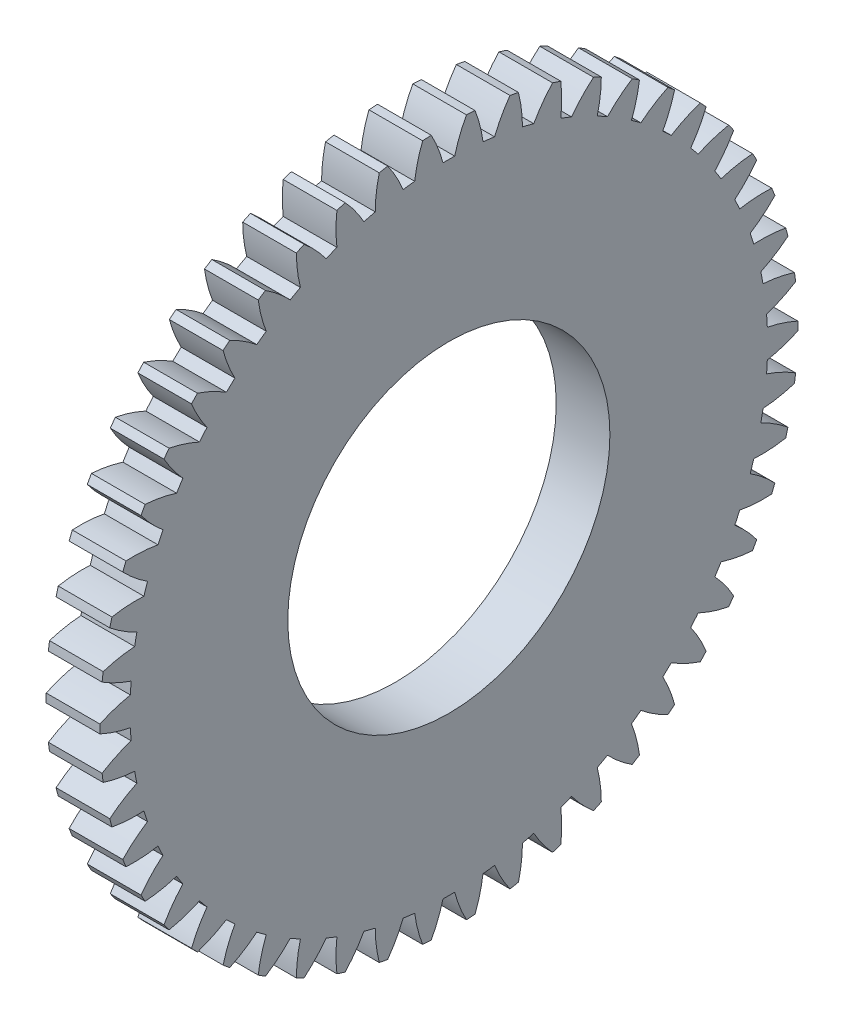
SolidWorks part; units mm, degrees
ref_plane "Plane1" through (0, 0, 0) normal (0, 0, 1) x (1, 0, 0)
ref_plane "Plane2" through (0, 0, 0) normal (0, 1, 0) x (1, 0, 0)
ref_plane "Plane3" through (0, 0, 0) normal (1, 0, 0) x (0, 0, -1)
other "Configuration Table"
sketch "HoldingSke" plane through (0, 0, 0) normal (0, 1, 0) x (1, 0, 0)
  line L0 (0, 0) -> (0.5142, -0.6128)
  line L1 (-15, 0) -> (100, 0) construction
  line L2 (0, 0) -> (-2.1039, 2.3779)
  line L3 (0, 0) -> (-11.863, 4.5341)
  line L4 (0, 0) -> (5.5511, 6.6156)
  line L5 (0, 0) -> (-46.8476, -17.4728)
  line L6 (0, 0) -> (-4.1448, -2.7965)
  line L7 (-2.1039, 2.3779) -> (8.6586, 51.2059)
  line L8 (-76.2, 54.61) -> (-72.9, 54.61)
  line L9 (-71.009, 38.7566) -> (-53.1078, 45.2721)
  line L10 (-76.2, 71.12) -> (104.1128, 71.12)
  line L11 (0, 0) -> (-5, 0)
  line L12 (-76.2, 101.6) -> (-76.155, 101.6)
  line L13 (24.9733, 27.94) -> (52.9518, 28.4284)
  line L14 (24.9733, 27.94) -> (24.9743, 27.94)
  line L15 (24.9733, 27.94) -> (100.4006, 29.5858)
  line L16 (-63.627, -1.25) -> (-12.827, -1.25)
  circle A0 centre (0, 0) radius 15
  circle A1 centre (0, 0) radius 29.6865
  circle A2 centre (0, 0) radius 37.5
  circle A3 centre (0, 0) radius 15
  dimension "MHD" = 59.373
  dimension "Hub_dia" = 75
  dimension "Bore" = 30
  dimension "MBD" = 30
  dimension "Num_teeth" = 50
  dimension "Pitch" = 0.8
  dimension "Overall_len" = 50
  dimension "Show_teeth" = 50
  dimension "Thickness" = 5
  dimension "OAL" = 50.0001
  dimension "T_dim" = 3.3
  dimension "Ap" = 20
  dimension "H" = 19.05
  dimension "Pitch_radius" = 180.3128
  dimension "Width" = 5
  dimension "Backlash" = 0.045
  dimension "Addendum_fac" = 1
  dimension "Dedendum_fac" = 1.25
  dimension "Clearance_fac" = 0.25
  dimension "Dedendum_add" = 0.001
  dimension "Module" = 1.25
sketch "BasProSke" plane through (0, 0, 0) normal (0, 1, 0) x (1, 0, 0)
  line L0 (-10, 0) -> (60, 0) construction
  line L1 (0, 0) -> (0, 32.5)
  line L2 (0, 0) -> (5, 0)
  line L3 (5, 0) -> (5, 32.5)
  line L4 (5, 32.5) -> (0, 32.5)
  dimension "Thickness" = 5
  dimension "Diameter" = 65
revolve "Base-Revolve" add sketch "BasProSke" angle 360 about L0
sketch "TooCutSke" plane through (0, 0, 0) normal (1, 0, 0) x (0, 0, -1)
  line L1 (0, 0) -> (0, 107) construction
  line L2 (0, 0) -> (-1.0603, 31.232) construction
  line L3 (0, 0) -> (-3.9228, 62.3506) construction
  line L4 (-1.0603, 31.232) -> (-1.9614, 31.1753) construction
  arc A0 (0.543, 29.6815) -> (-0.543, 29.6815) centre (0, 0) ccw
  arc A1 (1.6539, 32.4833) -> (-1.6539, 32.4833) centre (0, 0) ccw
  circle A2 centre (0, 0) radius 31.25 construction
  circle A3 centre (0, 0) radius 29.3654 construction
  arc A4 (-0.543, 29.6815) -> (-1.6539, 32.4833) centre (-12.6336, 26.5088) ccw
  arc A5 (1.6539, 32.4833) -> (0.543, 29.6815) centre (12.6336, 26.5088) ccw
  dimension "Root_dia" = 59.373
  dimension "Overcut_dia" = 65.0508
  dimension "Pitch_dia" = 62.5
  dimension "Base_dia" = 58.7308
  dimension "Flank_rad" = 12.5
  dimension "Half_ang" = 3.6
  dimension "Half_CT" = 0.9028
extrude "ToothCut" cut sketch "TooCutSke" along normal through all
fillet "Breaks" [suppressed] radius 0.025
fillet "RootFillets" [suppressed] radius 0.3135
pattern_circular "TeethCuts" count 50 every 7.2 about axis through (-10, 0, 0) along (1, 0, 0) of "ToothCut", "RootFillets", "Breaks"
sketch "HubNeaOneSke" plane through (0, 0, 0) normal (-1, 0, 0) x (0, 0, 1)
  circle A0 centre (0, 0) radius 29.6865
  dimension "Diameter" = 59.373
extrude "HubNearOne" [suppressed] add sketch "HubNeaOneSke" along normal blind 45.0001
sketch "HubNeaBotSke" plane through (0, 0, 0) normal (-1, 0, 0) x (0, 0, 1)
  circle A0 centre (0, 0) radius 29.6865
  dimension "Diameter" = 59.373
extrude "HubNearBoth" [suppressed] add sketch "HubNeaBotSke" along normal blind 22.5001
ref_plane "FarPln" through (5, 0, 0) normal (1, 0, 0) x (0, 0, -1)
sketch "HubFarSke" plane through (5, 0, 0) normal (1, 0, 0) x (0, 0, -1)
  circle A0 centre (0, 0) radius 29.6865
  dimension "Diameter" = 59.373
extrude "HubFar" [suppressed] add sketch "HubFarSke" along normal blind 22.5001
sketch "BorSke" plane through (0, 0, 0) normal (1, 0, 0) x (0, 0, -1)
  circle A0 centre (0, 0) radius 15
  dimension "Diameter" = 30
extrude "Bore" cut sketch "BorSke" along normal mid plane 100.0002
sketch "KeySke" plane through (0, 0, 0) normal (1, 0, 0) x (0, 0, -1)
  line L0 (-5, 0) -> (-5, 18.3)
  line L1 (-5, 18.3) -> (5, 18.3)
  line L2 (5, 18.3) -> (5, 0)
  line L3 (0, 0) -> (0, 34) construction
  line L4 (-5, 0) -> (5, 0)
  dimension "Offset" = 18.3
  dimension "Width" = 10
extrude "Keyway" [suppressed] cut sketch "KeySke" along normal mid plane 100.0002
pattern_circular "Keyway2" [suppressed] count 2 every 90 about axis through (-10, 0, 0) along (1, 0, 0)
equation "' \"Module@HoldingSke\" = 6.35"
equation "' \"Num_teeth@HoldingSke\" = 12"
equation "' \"Ap@HoldingSke\" =  20"
equation "' \"Ap@HoldingSke\" = 20"
equation "' \"Width@HoldingSke\" = 0.5 * 25.4"
equation "' \"Hub_dia@HoldingSke\"= 1 * 25.4"
equation "' \"Hub_dia@HoldingSke\" = 1 * 25.4"
equation "' \"Overall_len@HoldingSke\" = 1.0 * 25.4"
equation "' \"Bore@HoldingSke\" = 0.75 * 25.4"
equation "' \"T_dim@HoldingSke\" = 0.1 * 25.4"
equation "' \"Width@KeySke\" = 0.25 * 25.4"
equation "' \"Show_teeth@HoldingSke\" = 13"
equation "' \"Backlash@HoldingSke\" = 0.009 * 25.4"
equation "' \"Addendum_fac@HoldingSke\" = 1.0"
equation "' \"Dedendum_fac@HoldingSke\" = 1.25"
equation "' \"Dedendum_add@HoldingSke\" = 0.00005 * 25.4"
equation "' \"Clearance_fac@HoldingSke\" = 0.25"
equation "\"Pitch@HoldingSke\" = 1 / \"Module@HoldingSke\""
equation "\"Overcut_dia@TooCutSke\" = (\"Num_teeth@HoldingSke\" + 2 * \"Addendum_fac@HoldingSke\") / \"Pitch@HoldingSke\" + 0.002 * 25.4"
equation "\"Pitch_dia@TooCutSke\" = \"Num_teeth@HoldingSke\" / \"Pitch@HoldingSke\""
equation "\"Base_dia@TooCutSke\" = \"Num_teeth@HoldingSke\" / \"Pitch@HoldingSke\" * cos((\"Ap@HoldingSke\"  * 3.14159265 / 180))"
equation "\"Root_dia@TooCutSke\" = (\"Num_teeth@HoldingSke\" + 2) / \"Pitch@HoldingSke\" - 2 * (\"Addendum_fac@HoldingSke\" + \"Dedendum_fac@HoldingSke\") / \"Pitch@HoldingSke\" - \"Dedendum_add@HoldingSke\" * 2"
equation "\"Half_ang@TooCutSke\" = 180 / \"Num_teeth@HoldingSke\""
equation "\"Half_CT@TooCutSke\" = \"Num_teeth@HoldingSke\" / \"Pitch@HoldingSke\" * sin((3.14159265 / 2 / \"Num_teeth@HoldingSke\")) / 2 - 7 * \"Backlash@HoldingSke\" / 4"
equation "\"Flank_rad@TooCutSke\" = \"Num_teeth@HoldingSke\" / \"Pitch@HoldingSke\" / 5"
equation "\"Radius@RootFillets\" = \"Clearance_fac@HoldingSke\" / \"Pitch@HoldingSke\" + \"Dedendum_add@HoldingSke\""
equation "\"Break_rad@Breaks\" = 0.02 / \"Pitch@HoldingSke\""
equation "\"Thickness@HoldingSke\" = \"Width@HoldingSke\""
equation "\"OAL@HoldingSke\" = \"Thickness@HoldingSke\""
equation "\"MHD@HoldingSke\" = (\"Num_teeth@HoldingSke\" + 2) / \"Pitch@HoldingSke\" - 2 * (\"Addendum_fac@HoldingSke\" + \"Dedendum_fac@HoldingSke\")  / \"Pitch@HoldingSke\" - \"Dedendum_add@HoldingSke\" * 2"
equation "\"MBD@HoldingSke\" = (\"Num_teeth@HoldingSke\" + 2) / \"Pitch@HoldingSke\" - 2 * (\"Addendum_fac@HoldingSke\" + \"Dedendum_fac@HoldingSke\")  / \"Pitch@HoldingSke\" - \"Dedendum_add@HoldingSke\" * 2 - 0.002 * 25.4"
equation "\"MHD@HoldingSke\" = ((sgn( \"MHD@HoldingSke\" - \"Hub_dia@HoldingSke\" )-1)*( \"MHD@HoldingSke\" - \"Hub_dia@HoldingSke\" ))/-2+ \"Hub_dia@HoldingSke\""
equation "\"MBD@HoldingSke\" = ((sgn( \"MBD@HoldingSke\" - \"Bore@HoldingSke\" )-1)*( \"MBD@HoldingSke\" - \"Bore@HoldingSke\" ))/-2+ \"Bore@HoldingSke\""
equation "\"OAL@HoldingSke\" = ((sgn( \"OAL@HoldingSke\" - \"Overall_len@HoldingSke\" )+1)*( \"OAL@HoldingSke\" - \"Overall_len@HoldingSke\" ))/2 + \"Overall_len@HoldingSke\" + 0.000002 * 25.4"
equation "\"Num_teeth@TeethCuts\" = int( \"Show_teeth@HoldingSke\" ) + 1"
equation "\"Num_teeth@TeethCuts\" = ((sgn( \"Num_teeth@TeethCuts\" - \"Num_teeth@HoldingSke\" )-1)*( \"Num_teeth@TeethCuts\" - \"Num_teeth@HoldingSke\" ))/-2+ \"Num_teeth@HoldingSke\""
equation "\"Num_teeth@TeethCuts\" = ((sgn( \"Num_teeth@TeethCuts\" - 2.0)+1)*( \"Num_teeth@TeethCuts\" - 2.0))/2 +2.0"
equation "\"Angle@TeethCuts\" = 360.0 / \"Num_teeth@HoldingSke\""
equation "\"Diameter@BasProSke\" = (\"Num_teeth@HoldingSke\" + 2 * \"Addendum_fac@HoldingSke\") / \"Pitch@HoldingSke\""
equation "\"Thickness@BasProSke\"  = \"Thickness@HoldingSke\""
equation "' \"Fillet_rad@BasProSke\" =  \"Thickness@HoldingSke\" * 0.05"
equation "' \"Fillet_rad@BasProSke\" = \"Thickness@HoldingSke\" * 0.05"
equation "\"MHD@HoldingSke\" = ((sgn( \"MHD@HoldingSke\" - \"Root_dia@TooCutSke\" )-1)*( \"MHD@HoldingSke\" - \"Root_dia@TooCutSke\" ))/-2+ \"Root_dia@TooCutSke\""
equation "\"Diameter@HubNeaOneSke\" = \"MHD@HoldingSke\""
equation "\"Length@HubNearOne\" = \"OAL@HoldingSke\" - \"Thickness@BasProSke\""
equation "\"Diameter@HubNeaBotSke\" = \"MHD@HoldingSke\""
equation "\"Length@HubNearBoth\" = ( \"OAL@HoldingSke\" - \"Thickness@BasProSke\" ) / 2.0"
equation "\"Thickness@FarPln\" = \"Thickness@BasProSke\""
equation "\"Diameter@HubFarSke\" = \"MHD@HoldingSke\""
equation "\"Length@HubFar\" = ( \"OAL@HoldingSke\" - \"Thickness@BasProSke\" ) / 2.0"
equation "\"Diameter@BorSke\" = \"MBD@HoldingSke\""
equation "\"D1@Bore\" = \"OAL@HoldingSke\" * 2.0"
equation "\"D1@Keyway\" = \"OAL@HoldingSke\" * 2.0"
equation "\"Offset@KeySke\" = \"T_dim@HoldingSke\" + \"MBD@HoldingSke\" / 2.0"
